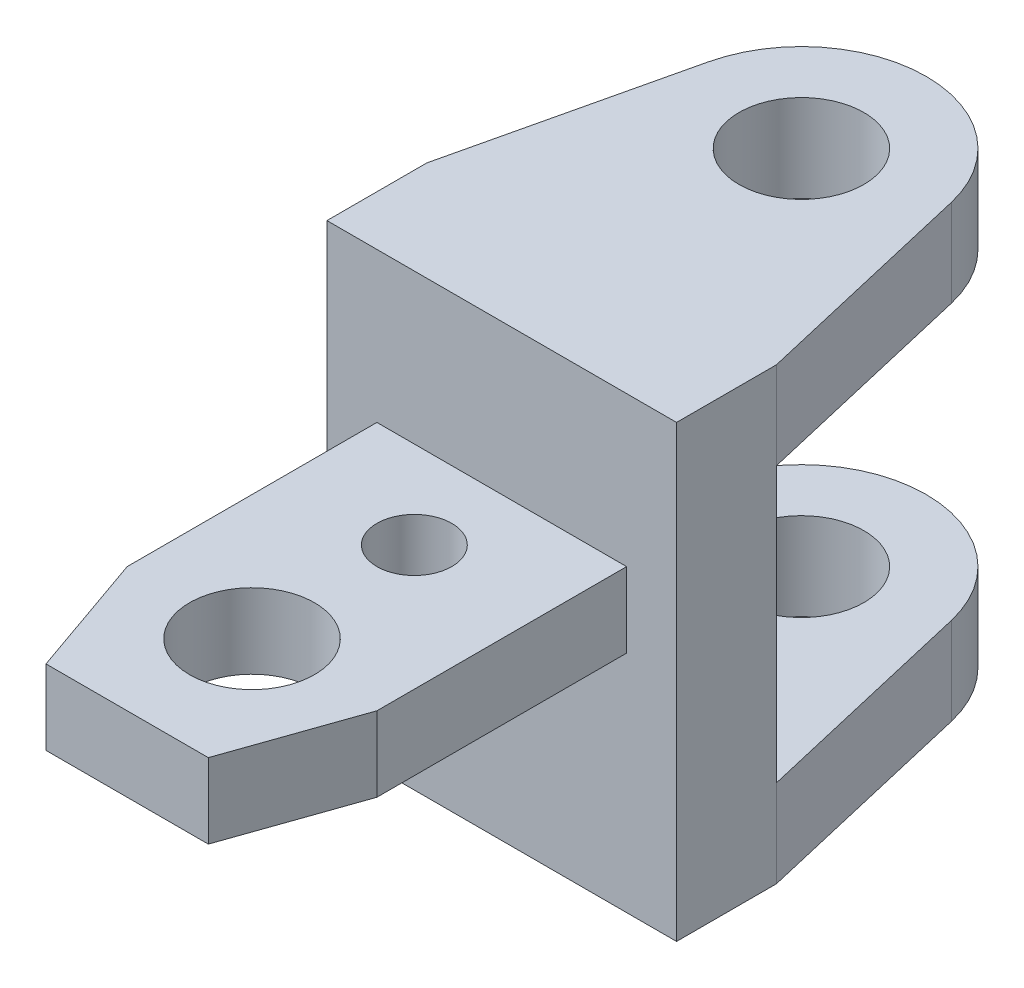
SolidWorks part; units mm, degrees
ref_plane "Front Plane" through (0, 0, 0) normal (0, 0, 1) x (1, 0, 0)
ref_plane "Top Plane" through (0, 0, 0) normal (0, 1, 0) x (1, 0, 0)
ref_plane "Right Plane" through (0, 0, 0) normal (1, 0, 0) x (0, 0, -1)
sketch "Sketch1" plane through (0, 0, 0) normal (0, 0, 1) x (1, 0, 0)
  line L1 (-14, -18) -> (14, -18)
  line L2 (-14, -18) -> (-14, 18)
  line L3 (-14, 18) -> (14, 18)
  line L4 (14, -18) -> (14, 18)
  line L5 (-14, -18) -> (14, 18) construction
  line L6 (-14, 18) -> (14, -18) construction
  point P0 (0, 0)
  point P6 (0, 0)
  dimension "D1" = 28
  dimension "D2" = 36
extrude "Boss-Extrude2" add sketch "Sketch1" against normal blind 8
sketch "Sketch3" plane through (0, 18, 0) normal (0, 1, 0) x (1, 0, 0)
  line L0 (-14, 8) -> (14, 8)
  line L1 (14, 8) -> (9.7386, 26.2713)
  line L2 (-9.7386, 26.2713) -> (-14, 8)
  line L3 (0, 8) -> (0, 39.4073) construction
  line L4 (14, 0) -> (-14, 0) construction
  arc A0 (9.7386, 26.2713) -> (-9.7386, 26.2713) centre (0, 24) ccw
  circle A1 centre (0, 24) radius 5
  dimension "D1" = 10
  dimension "D2" = 10
  dimension "D3" = 24
extrude "Boss-Extrude3" add sketch "Sketch3" against normal blind 7
mirror "Mirror1" about plane through (0, 0, 0) normal (0, 1, 0) of "Boss-Extrude3"
sketch "Sketch4" plane through (0, 0, 0) normal (1, 0, 0) x (0, 0, -1)
  line L0 (8, 18) -> (0, 18) construction
  line L1 (-30, 0) -> (0, 0)
  line L2 (-30, 0) -> (-30, 6)
  line L3 (-30, 6) -> (0, 6)
  line L4 (0, 0) -> (0, 6)
  line L5 (-30, 0) -> (0, 6) construction
  line L6 (-30, 6) -> (0, 0) construction
  line L7 (0, -18) -> (0, 18) construction
  point P0 (-15, 3)
  dimension "D1" = 12
  dimension "D2" = 6
  dimension "D3" = 30
extrude "Boss-Extrude4" add sketch "Sketch4" along normal mid plane 20
chamfer "Chamfer1" distance 10 distance2 3.5 1 edges at (-10, 3, 30)
chamfer "Chamfer2" distance 3.5 distance2 10 1 edges at (10, 3, 30)
sketch "Sketch5" plane through (0, 6, 0) normal (0, 1, 0) x (1, 0, 0)
  line L0 (0, 0) -> (0, -30) construction
  line L1 (6.5, -30) -> (-6.5, -30) construction
  line L2 (10, 0) -> (-10, 0) construction
  circle A0 centre (0, -7) radius 3
  circle A1 centre (0, -20) radius 5
  dimension "D2" = 6
  dimension "D4" = 10
  dimension "D1" = 7
  dimension "D3" = 13
extrude "Cut-Extrude1" cut sketch "Sketch5" against normal up to next
